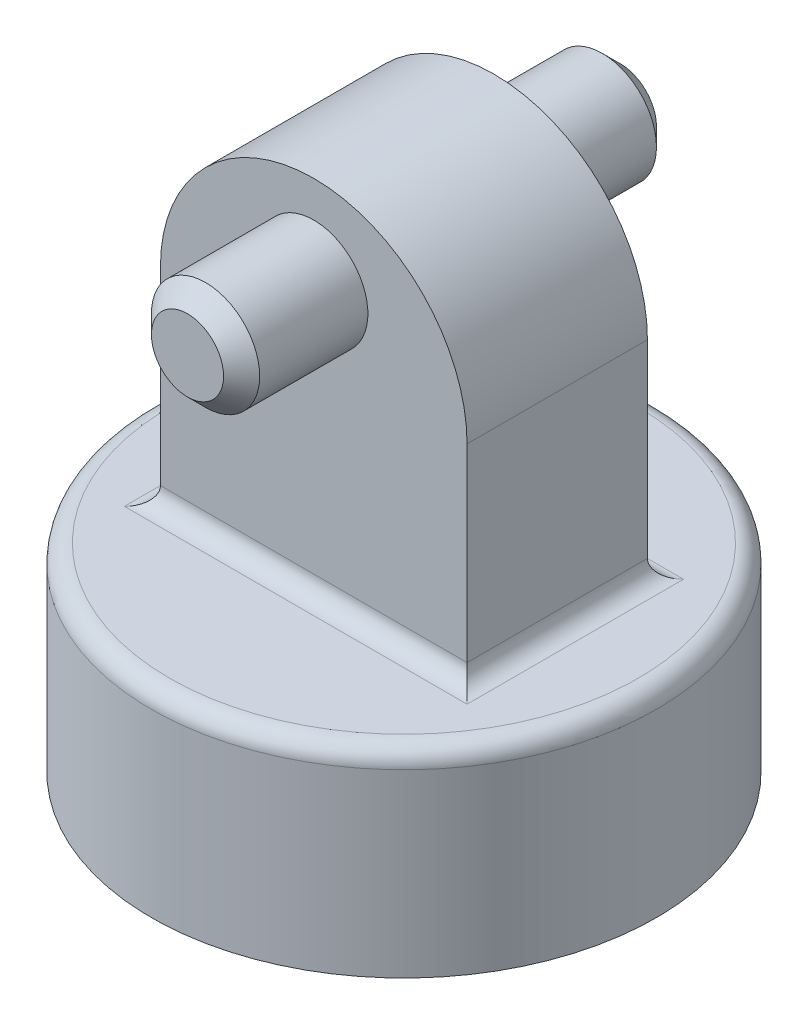
SolidWorks part; units mm, degrees
material "BUTYL"
ref_plane "Plan de face" through (0, 0, 0) normal (0, 0, 1) x (1, 0, 0)
ref_plane "Plan de dessus" through (0, 0, 0) normal (0, 1, 0) x (1, 0, 0)
ref_plane "Plan de droite" through (0, 0, 0) normal (1, 0, 0) x (0, 0, -1)
sketch "Esquisse1" plane through (0, 0, 0) normal (0, 0, 1) x (1, 0, 0)
  line L0 (0, 0) -> (0, 11) construction
  line L1 (-12, 0) -> (-12, 9)
  line L2 (-12, 9) -> (0, 9)
  line L3 (-12, 0) -> (-14, 0)
  line L4 (-14, 0) -> (-14, 11)
  line L5 (-14, 11) -> (0, 11)
  line L6 (0, 11) -> (0, 9)
  dimension "D1" = 2
  dimension "D2" = 24
  dimension "D3" = 9
  dimension "D4" = 2
revolve "Révolution1" add sketch "Esquisse1" angle 360 about L0
fillet "Congé1" radius 1 1 edges at (0, 11, -14)
sketch "Esquisse2" plane through (0, 11, 0) normal (0, 1, 0) x (1, 0, 0)
  line L1 (-8.5, -5) -> (8.5, -5)
  line L2 (-8.5, -5) -> (-8.5, 5)
  line L3 (-8.5, 5) -> (8.5, 5)
  line L4 (8.5, -5) -> (8.5, 5)
  line L5 (-8.5, -5) -> (8.5, 5) construction
  line L6 (-8.5, 5) -> (8.5, -5) construction
  point P0 (0, 0)
  dimension "D1" = 17
  dimension "D2" = 10
extrude "Boss.-Extru.1" add sketch "Esquisse2" along normal blind 20
fillet "Congé2" radius 1 4 edges at (0, 11, -5) (-8.5, 11, 0) (0, 11, 5) (8.5, 11, 0)
sketch "Esquisse3" plane through (0, 0, 5) normal (0, 0, 1) x (1, 0, 0)
  line L0 (-8.5, 31) -> (-8.5, 12) construction
  line L1 (8.5, 31) -> (8.5, 12) construction
  line L2 (-8.5, 31) -> (8.5, 31) construction
  line L3 (8.5, 22.5) -> (8.5, 31)
  line L4 (8.5, 31) -> (-8.5, 31)
  line L5 (-8.5, 31) -> (-8.5, 22.5)
  arc A0 (-8.5, 22.5) -> (8.5, 22.5) centre (0, 22.5) cw
  line M1 (-8.5, 31) -> (-8.5, 12)
  line M3 (8.5, 12) -> (8.5, 31)
  line M4 (8.5, 31) -> (-8.5, 31)
extrude "Enlèv. mat.-Extru.1" cut sketch "Esquisse3" against normal up to next contours A0 L4 M1 | A0 M4 M3
sketch "Esquisse5" plane through (0, 0, 5) normal (0, 0, 1) x (1, 0, 0)
  circle A1 centre (0, 26) radius 3
  arc A2 (8.5, 22.5) -> (-8.5, 22.5) centre (0, 22.5) ccw construction
  dimension "D1" = 6
  dimension "D2" = 3.5
extrude "Boss.-Extru.2" add sketch "Esquisse5" along normal blind 7
chamfer "Chanfrein1" distance 1 angle 45 1 edges at (3, 26, 12)
mirror "Symétrie4" about plane through (0, 0, 0) normal (0, 0, 1) of "Boss.-Extru.2"
chamfer "Chanfrein2" distance 1 angle 45 1 edges at (3, 26, -12)
